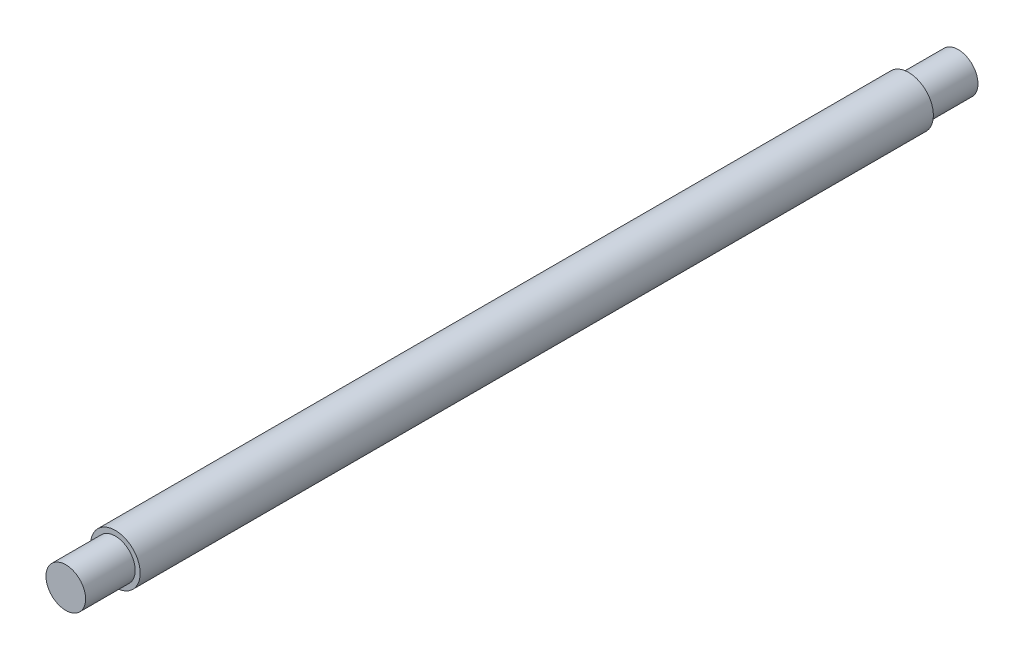
SolidWorks part; units mm, degrees
ref_plane "前视基准面" through (0, 0, 0) normal (0, 0, 1) x (1, 0, 0)
ref_plane "上视基准面" through (0, 0, 0) normal (0, 1, 0) x (1, 0, 0)
ref_plane "右视基准面" through (0, 0, 0) normal (1, 0, 0) x (0, 0, -1)
sketch "草图1" plane through (0, 0, 0) normal (0, 0, 1) x (1, 0, 0)
  circle A0 centre (-0.6402, 5.2815) radius 2.5
  dimension "D1" = 5
extrude "凸台-拉伸1" add sketch "草图1" along normal blind 80
sketch "草图2" plane through (0, 0, 80) normal (0, 0, 1) x (1, 0, 0)
  line L0 (-0.6402, 7.7815) -> (-0.6402, 2.7815) construction
  circle A0 centre (-0.6402, 5.2815) radius 2.5 construction
  circle A1 centre (-0.6402, 5.2815) radius 2
  dimension "D1" = 4
extrude "凸台-拉伸2" add sketch "草图2" along normal blind 5
sketch "草图3" plane through (0, 0, 0) normal (0, 0, -1) x (-1, 0, 0)
  line L0 (0.6402, 7.7815) -> (0.6402, 2.7815) construction
  circle A0 centre (0.6402, 5.2815) radius 2.5 construction
  circle A1 centre (0.6402, 5.2815) radius 2
  dimension "D1" = 4
extrude "凸台-拉伸3" add sketch "草图3" along normal blind 5
